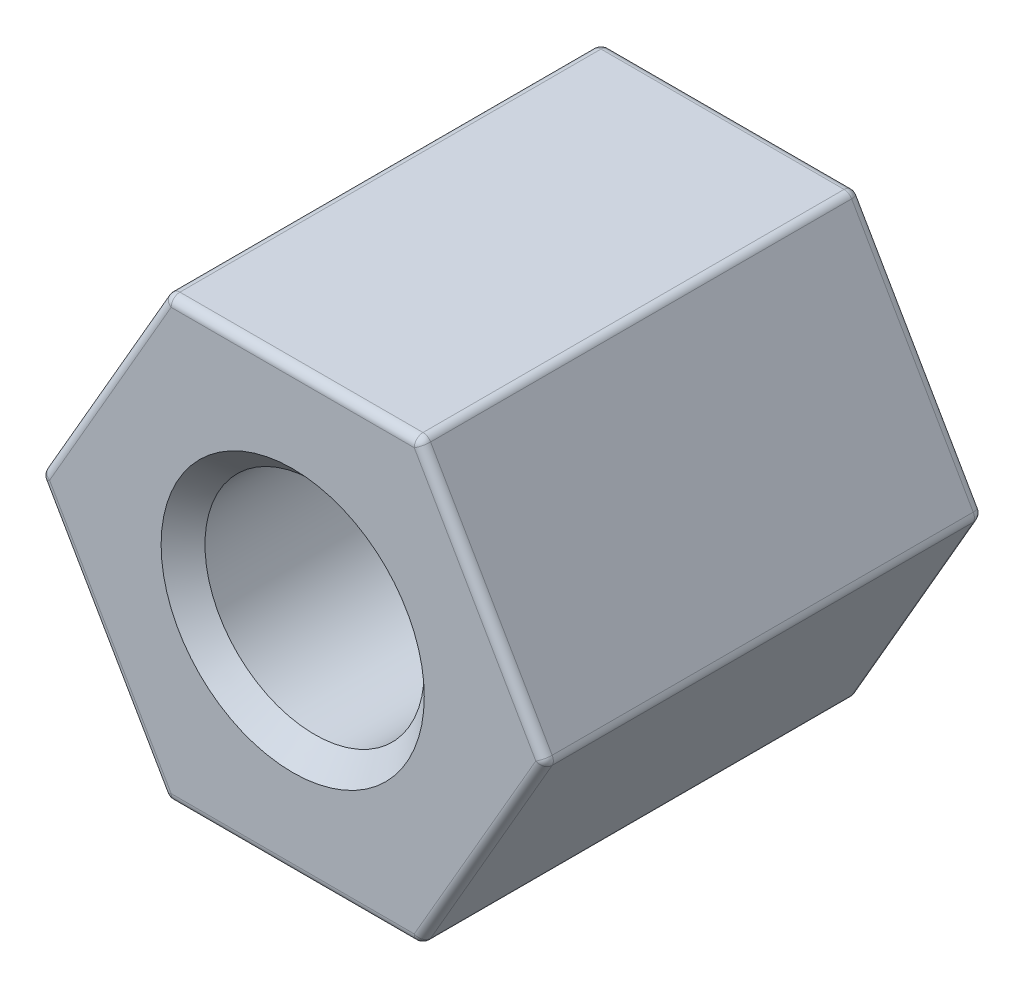
SolidWorks part; units mm, degrees
material "Латунь"
ref_plane "Спереди" through (0, 0, 0) normal (0, 0, 1) x (1, 0, 0)
ref_plane "Сверху" through (0, 0, 0) normal (0, 1, 0) x (1, 0, 0)
ref_plane "Справа" through (0, 0, 0) normal (1, 0, 0) x (0, 0, -1)
sketch "Эскиз1" plane through (0, 0, 0) normal (0, 0, 1) x (1, 0, 0)
  line L1 (2.8868, 0) -> (1.4434, 2.5)
  line L2 (1.4434, 2.5) -> (-1.4434, 2.5)
  line L3 (-1.4434, 2.5) -> (-2.8868, 0)
  line L4 (-2.8868, 0) -> (-1.4434, -2.5)
  line L5 (-1.4434, -2.5) -> (1.4434, -2.5)
  line L6 (1.4434, -2.5) -> (2.8868, 0)
  circle A0 centre (0, 0) radius 2.5 construction
  dimension "H1" = 5
extrude "Бобышка-Вытянуть1" add sketch "Эскиз1" along normal blind 5
sketch "Эскиз2" plane through (0, 0, 5) normal (0, 0, 1) x (1, 0, 0)
  circle A0 centre (0, 0) radius 1.25
  dimension "D1" = 2.5
extrude "Вырез-Вытянуть1" cut sketch "Эскиз2" against normal blind 2.5
cosmetic thread "Условное изображение резьбы1" parameters "P1"=2.5, "Dr1"=3
sketch "Эскиз3" plane through (0, 0, 0) normal (0, 0, -1) x (-1, 0, 0)
  circle A0 centre (0, 0) radius 1.25
  dimension "D2" = 2.5
extrude "Вырез-Вытянуть2" cut sketch "Эскиз3" against normal blind 2.5
cosmetic thread "Условное изображение резьбы2" parameters "P2"=2.5, "Dr2"=3
chamfer "Фаска1" distance 0.25 2 edges at (-1.25, 0, 0) (1.25, 0, 5)
fillet "Скругление1" radius 0.1 18 edges at (-2.1651, 1.25, 5) (-2.1651, 1.25, 0) (-2.8868, 0, 2.5) (-2.1651, -1.25, 5) (-2.1651, -1.25, 0) (-1.4434, -2.5, 2.5) (0, -2.5, 5) (0, -2.5, 0) (1.4434, -2.5, 2.5) (2.1651, -1.25, 5) (2.1651, -1.25, 0) (2.8868, 0, 2.5) (2.1651, 1.25, 5) (2.1651, 1.25, 0) (1.4434, 2.5, 2.5) (0, 2.5, 5) (-1.4434, 2.5, 2.5) (0, 2.5, 0)
